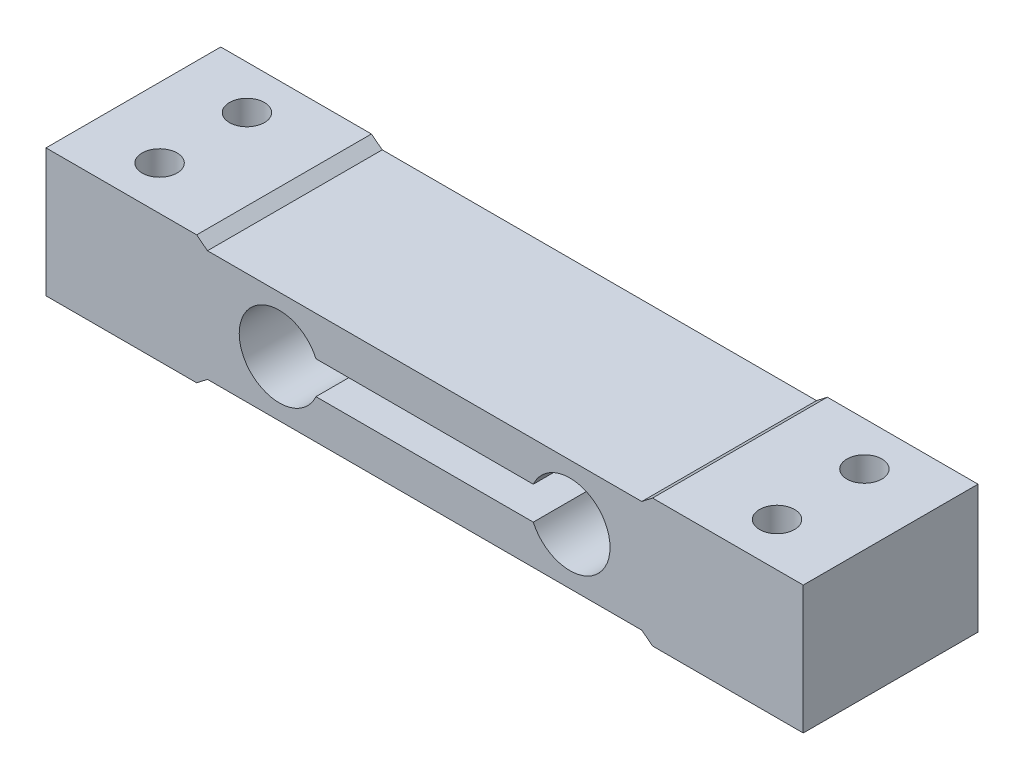
SolidWorks part; units mm, degrees
ref_plane "Front Plane" through (0, 0, 0) normal (0, 0, 1) x (1, 0, 0)
ref_plane "Top Plane" through (0, 0, 0) normal (0, 1, 0) x (1, 0, 0)
ref_plane "Right Plane" through (0, 0, 0) normal (1, 0, 0) x (0, 0, -1)
sketch "Sketch2" plane through (0, 0, 0) normal (0, 0, 1) x (1, 0, 0)
  line L0 (-65, 11) -> (-65, -11)
  line L1 (-65, -11) -> (-39.13, -11)
  line L2 (-39.13, -11) -> (-37.28, -9.565)
  line L3 (-37.28, -9.565) -> (37.28, -9.565)
  line L4 (37.28, -9.565) -> (39.13, -11)
  line L5 (39.13, -11) -> (65, -11)
  line L6 (65, -11) -> (65, 11)
  line L7 (65, 11) -> (39.13, 11)
  line L8 (39.13, 11) -> (37.28, 9.565)
  line L9 (37.28, 9.565) -> (-37.28, 9.565)
  line L12 (-37.28, 9.565) -> (-39.13, 11)
  line L13 (-39.13, 11) -> (-65, 11)
  line L14 (-65, 0) -> (65, 0) construction
  line L15 (0, 9.565) -> (0, -9.565) construction
  line L16 (0, 2.815) -> (18.655, 2.815)
  line L17 (18.655, -2.815) -> (0, -2.815)
  line L18 (-18.655, -2.815) -> (0, -2.815)
  line L19 (0, 2.815) -> (-18.655, 2.815)
  line L20 (18.655, 2.815) -> (18.655, -2.815) construction
  line L21 (37.28, 9.565) -> (37.28, -9.565) construction
  arc A1 (18.655, 2.815) -> (18.655, -2.815) centre (24.9418, 0) cw
  arc A2 (-18.655, 2.815) -> (-18.655, -2.815) centre (-24.9418, 0) ccw
  point P14 (0, 0)
  point P26 (18.655, 0)
  dimension "D7" = 63.66
  dimension "D1" = 22
  dimension "D2" = 130
  dimension "D3" = 5.63
  dimension "D4" = 19.13
  dimension "D5" = 78.26
  dimension "D6" = 74.56
  dimension "D8" = 37.31
extrude "Boss-Extrude1" add sketch "Sketch2" along normal mid plane 30
sketch "Sketch5" plane through (0, 11, 0) normal (0, 1, 0) x (1, 0, 0)
  line L0 (-65, 0) -> (-39.13, 0) construction
  line L2 (-57.602, 7.5) -> (-48.398, 7.5) construction
  line L3 (-57.602, -7.5) -> (-48.398, -7.5) construction
  line L4 (-39.13, 15) -> (-65, 15)
  line L5 (-65, 15) -> (-65, -15)
  line L6 (-65, -15) -> (-39.13, -15)
  line L7 (-39.13, -15) -> (-39.13, 15)
  line L8 (-39.13, 15) -> (-65, 15)
  line L9 (-65, 15) -> (-65, -15)
  line L10 (-65, -15) -> (-39.13, -15)
  line L11 (-39.13, -15) -> (-39.13, 15)
  line L12 (0, 15) -> (0, -15) construction
  line L13 (37.28, 15) -> (-37.28, 15) construction
  line L14 (37.28, -15) -> (-37.28, -15) construction
  line L15 (57.602, -7.5) -> (48.398, -7.5) construction
  line L16 (57.602, 7.5) -> (48.398, 7.5) construction
  line L17 (52.065, 15) -> (52.065, -15) construction
  line L18 (65, 0) -> (39.13, 0) construction
  circle A0 centre (-53, 7.5) radius 3
  circle A1 centre (-53, -7.5) radius 3
  circle A2 centre (53, -7.5) radius 3
  circle A3 centre (53, 7.5) radius 3
  point P7 (-65, 0)
  point P8 (-39.13, 0)
  point P14 (-53, 7.5)
  point P17 (-53, 7.5)
  point P26 (0, 15)
  point P30 (0, -15)
  point P43 (-53, 7.5)
  point P44 (53, 7.5)
  dimension "D3" = 6
  dimension "D2" = 15
  dimension "D4" = 106
  dimension "D1" = 0
extrude "Cut-Extrude1" cut sketch "Sketch5" against normal through all contours A1 | A0 | A2 | A3
